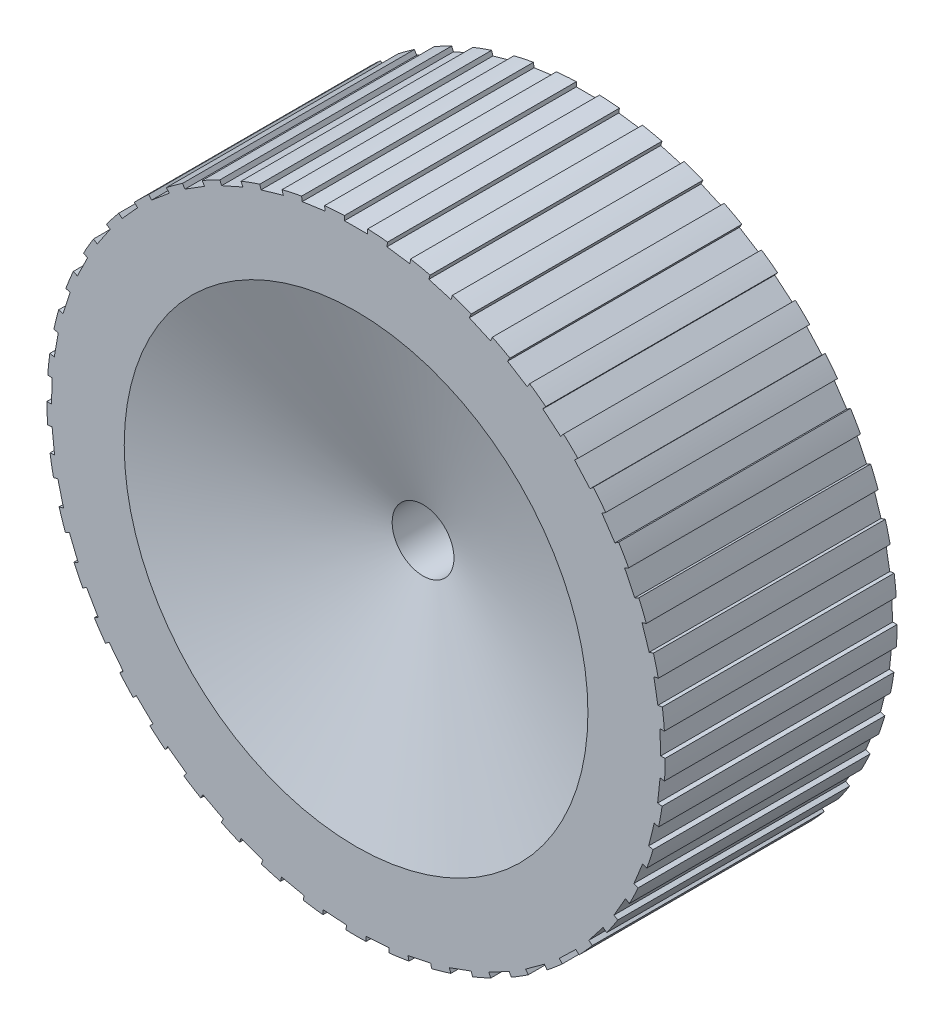
SolidWorks part; units mm, degrees
ref_plane "Front Plane" through (0, 0, 0) normal (0, 0, 1) x (1, 0, 0)
ref_plane "Top Plane" through (0, 0, 0) normal (0, 1, 0) x (1, 0, 0)
ref_plane "Right Plane" through (0, 0, 0) normal (1, 0, 0) x (0, 0, -1)
sketch "Sketch1" plane through (0, 0, 0) normal (0, 0, 1) x (1, 0, 0)
  circle A0 centre (0, 0) radius 40
  circle A1 centre (0, 0) radius 4
  dimension "D1" = 80
  dimension "D2" = 8
extrude "Boss-Extrude1" add sketch "Sketch1" along normal blind 30
sketch "Sketch3" plane through (0, 0, 0) normal (1, 0, 0) x (0, 0, -1)
  line L0 (-15, 40) -> (-15, -40) construction
  line L1 (0, 40) -> (-30, 40) construction
  line L2 (-30, -40) -> (0, -40) construction
  line L3 (0, 0) -> (-30, 0) construction
  line L4 (-30, 40) -> (-30, -40) construction
  line L5 (-30, 30) -> (0, 30) construction
  line L6 (0, -40) -> (0, 40) construction
  line L7 (0, 30) -> (-10, 0)
  line L8 (0, 30) -> (2.6052, 27.3948)
  line L9 (2.6052, 27.3948) -> (2.6052, 0)
  line L10 (2.6052, 0) -> (-10, 0)
  line L11 (-32.6052, 0) -> (-20, 0)
  line L12 (-30, 30) -> (-20, 0)
  line L13 (-32.6052, 27.3948) -> (-32.6052, 0)
  line L14 (-30, 30) -> (-32.6052, 27.3948)
  dimension "D1" = 10
  dimension "D2" = 5
revolve "Cut-Revolve1" cut sketch "Sketch3" angle 360 about L10
sketch "Sketch4" plane through (0, 0, 30) normal (0, 0, 1) x (1, 0, 0)
  line L0 (0, 40) -> (0, -40) construction
  line L1 (7.1372, 40.0061) -> (6.9674, 38.7978)
  line L2 (-1.5, 40.6101) -> (1.5, 40.6101)
  line L3 (-1.5, 40.6101) -> (-1.5, 39.3899)
  line L4 (-1.5, 39.3899) -> (1.5, 39.3899)
  line L5 (1.5, 40.6101) -> (1.5, 39.3899)
  line L6 (-1.5, 40.6101) -> (1.5, 39.3899) construction
  line L7 (-1.5, 39.3899) -> (1.5, 40.6101) construction
  line L8 (3.9966, 39.2153) -> (6.9674, 38.7978)
  line L9 (4.1664, 40.4236) -> (3.9966, 39.2153)
  line L10 (4.1664, 40.4236) -> (7.1372, 40.0061)
  line L11 (12.6356, 38.6235) -> (12.2992, 37.4505)
  line L12 (9.4154, 38.2775) -> (12.2992, 37.4505)
  line L13 (9.7518, 39.4504) -> (9.4154, 38.2775)
  line L14 (9.7518, 39.4504) -> (12.6356, 38.6235)
  line L15 (17.8879, 36.4891) -> (17.3916, 35.3744)
  line L16 (14.651, 36.5946) -> (17.3916, 35.3744)
  line L17 (15.1473, 37.7093) -> (14.651, 36.5946)
  line L18 (15.1473, 37.7093) -> (17.8879, 36.4891)
  line L19 (22.7921, 33.6444) -> (22.1455, 32.6096)
  line L20 (19.6014, 34.1994) -> (22.1455, 32.6096)
  line L21 (20.248, 35.2342) -> (19.6014, 34.1994)
  line L22 (20.248, 35.2342) -> (22.7921, 33.6444)
  line L23 (27.2527, 30.145) -> (26.4684, 29.2102)
  line L24 (24.1703, 31.1386) -> (26.4684, 29.2102)
  line L25 (24.9546, 32.0733) -> (24.1703, 31.1386)
  line L26 (24.9546, 32.0733) -> (27.2527, 30.145)
  line L27 (31.1829, 26.0587) -> (30.2761, 25.2423)
  line L28 (28.2687, 27.4717) -> (30.2761, 25.2423)
  line L29 (29.1755, 28.2882) -> (28.2687, 27.4717)
  line L30 (29.1755, 28.2882) -> (31.1829, 26.0587)
  line L31 (34.5061, 21.4653) -> (33.4945, 20.783)
  line L32 (31.8169, 23.2701) -> (33.4945, 20.783)
  line L33 (32.8285, 23.9524) -> (31.8169, 23.2701)
  line L34 (32.8285, 23.9524) -> (34.5061, 21.4653)
  line L35 (37.1577, 16.4541) -> (36.061, 15.9192)
  line L36 (34.7458, 18.6156) -> (36.061, 15.9192)
  line L37 (35.8426, 19.1505) -> (34.7458, 18.6156)
  line L38 (35.8426, 19.1505) -> (37.1577, 16.4541)
  line L39 (39.086, 11.1226) -> (37.9255, 10.7456)
  line L40 (36.9985, 13.5987) -> (37.9255, 10.7456)
  line L41 (38.159, 13.9758) -> (36.9985, 13.5987)
  line L42 (38.159, 13.9758) -> (39.086, 11.1226)
  line L43 (40.2536, 5.5747) -> (39.0519, 5.3628)
  line L44 (38.531, 8.3172) -> (39.0519, 5.3628)
  line L45 (39.7327, 8.5291) -> (38.531, 8.3172)
  line L46 (39.7327, 8.5291) -> (40.2536, 5.5747)
  line L47 (40.6377, -0.0818) -> (39.4183, -0.1244)
  line L48 (39.3136, 2.8738) -> (39.4183, -0.1244)
  line L49 (40.533, 2.9164) -> (39.3136, 2.8738)
  line L50 (40.533, 2.9164) -> (40.6377, -0.0818)
  line L51 (40.2308, -5.7367) -> (39.0173, -5.6091)
  line L52 (39.3309, -2.6256) -> (39.0173, -5.6091)
  line L53 (40.5444, -2.7531) -> (39.3309, -2.6256)
  line L54 (40.5444, -2.7531) -> (40.2308, -5.7367)
  line L55 (39.0409, -11.2799) -> (37.857, -10.9847)
  line L56 (38.5827, -8.0738) -> (37.857, -10.9847)
  line L57 (39.7667, -8.369) -> (38.5827, -8.0738)
  line L58 (39.7667, -8.369) -> (39.0409, -11.2799)
  line L59 (37.0911, -16.6036) -> (35.9598, -16.1465)
  line L60 (37.0836, -13.3649) -> (35.9598, -16.1465)
  line L61 (38.2149, -13.822) -> (37.0836, -13.3649)
  line L62 (38.2149, -13.822) -> (37.0911, -16.6036)
  line L63 (34.4194, -21.6041) -> (33.3627, -20.994)
  line L64 (34.8627, -18.3959) -> (33.3627, -20.994)
  line L65 (35.9194, -19.006) -> (34.8627, -18.3959)
  line L66 (35.9194, -19.006) -> (34.4194, -21.6041)
  line L67 (31.0777, -26.1841) -> (30.1162, -25.4329)
  line L68 (31.9632, -23.0688) -> (30.1162, -25.4329)
  line L69 (32.9247, -23.8201) -> (31.9632, -23.0688)
  line L70 (32.9247, -23.8201) -> (31.0777, -26.1841)
  line L71 (27.1311, -30.2544) -> (26.2835, -29.3767)
  line L72 (28.4415, -27.2927) -> (26.2835, -29.3767)
  line L73 (29.2892, -28.1705) -> (28.4415, -27.2927)
  line L74 (29.2892, -28.1705) -> (27.1311, -30.2544)
  line L75 (22.6565, -33.7359) -> (21.9393, -32.7488)
  line L76 (24.3663, -30.9854) -> (21.9393, -32.7488)
  line L77 (25.0835, -31.9726) -> (24.3663, -30.9854)
  line L78 (25.0835, -31.9726) -> (22.6565, -33.7359)
  line L79 (17.7409, -36.5608) -> (17.168, -35.4834)
  line L80 (19.8169, -34.075) -> (17.168, -35.4834)
  line L81 (20.3897, -35.1524) -> (19.8169, -34.075)
  line L82 (20.3897, -35.1524) -> (17.7409, -36.5608)
  line L83 (12.4799, -38.674) -> (12.0626, -37.5274)
  line L84 (14.8817, -36.5014) -> (12.0626, -37.5274)
  line L85 (15.299, -37.648) -> (14.8817, -36.5014)
  line L86 (15.299, -37.648) -> (12.4799, -38.674)
  line L87 (6.9761, -40.0345) -> (6.7224, -38.841)
  line L88 (9.6568, -38.2173) -> (6.7224, -38.841)
  line L89 (9.9105, -39.4108) -> (9.6568, -38.2173)
  line L90 (9.9105, -39.4108) -> (6.9761, -40.0345)
  line L91 (1.3365, -40.6158) -> (1.2514, -39.3986)
  line L92 (4.244, -39.1893) -> (1.2514, -39.3986)
  line L93 (4.3292, -40.4065) -> (4.244, -39.1893)
  line L94 (4.3292, -40.4065) -> (1.3365, -40.6158)
  line L95 (-4.3292, -40.4065) -> (-4.244, -39.1893)
  line L96 (-1.2514, -39.3986) -> (-4.244, -39.1893)
  line L97 (-1.3365, -40.6158) -> (-1.2514, -39.3986)
  line L98 (-1.3365, -40.6158) -> (-4.3292, -40.4065)
  line L99 (-9.9105, -39.4108) -> (-9.6568, -38.2173)
  line L100 (-6.7224, -38.841) -> (-9.6568, -38.2173)
  line L101 (-6.9761, -40.0345) -> (-6.7224, -38.841)
  line L102 (-6.9761, -40.0345) -> (-9.9105, -39.4108)
  line L103 (-15.299, -37.648) -> (-14.8817, -36.5014)
  line L104 (-12.0626, -37.5274) -> (-14.8817, -36.5014)
  line L105 (-12.4799, -38.674) -> (-12.0626, -37.5274)
  line L106 (-12.4799, -38.674) -> (-15.299, -37.648)
  line L107 (-20.3897, -35.1524) -> (-19.8169, -34.075)
  line L108 (-17.168, -35.4834) -> (-19.8169, -34.075)
  line L109 (-17.7409, -36.5608) -> (-17.168, -35.4834)
  line L110 (-17.7409, -36.5608) -> (-20.3897, -35.1524)
  line L111 (-25.0835, -31.9726) -> (-24.3663, -30.9854)
  line L112 (-21.9393, -32.7488) -> (-24.3663, -30.9854)
  line L113 (-22.6565, -33.7359) -> (-21.9393, -32.7488)
  line L114 (-22.6565, -33.7359) -> (-25.0835, -31.9726)
  line L115 (-29.2892, -28.1705) -> (-28.4415, -27.2927)
  line L116 (-26.2835, -29.3767) -> (-28.4415, -27.2927)
  line L117 (-27.1311, -30.2544) -> (-26.2835, -29.3767)
  line L118 (-27.1311, -30.2544) -> (-29.2892, -28.1705)
  line L119 (-32.9247, -23.8201) -> (-31.9632, -23.0688)
  line L120 (-30.1162, -25.4329) -> (-31.9632, -23.0688)
  line L121 (-31.0777, -26.1841) -> (-30.1162, -25.4329)
  line L122 (-31.0777, -26.1841) -> (-32.9247, -23.8201)
  line L123 (-35.9194, -19.006) -> (-34.8627, -18.3959)
  line L124 (-33.3627, -20.994) -> (-34.8627, -18.3959)
  line L125 (-34.4194, -21.6041) -> (-33.3627, -20.994)
  line L126 (-34.4194, -21.6041) -> (-35.9194, -19.006)
  line L127 (-38.2149, -13.822) -> (-37.0836, -13.3649)
  line L128 (-35.9598, -16.1465) -> (-37.0836, -13.3649)
  line L129 (-37.0911, -16.6036) -> (-35.9598, -16.1465)
  line L130 (-37.0911, -16.6036) -> (-38.2149, -13.822)
  line L131 (-39.7667, -8.369) -> (-38.5827, -8.0738)
  line L132 (-37.857, -10.9847) -> (-38.5827, -8.0738)
  line L133 (-39.0409, -11.2799) -> (-37.857, -10.9847)
  line L134 (-39.0409, -11.2799) -> (-39.7667, -8.369)
  line L135 (-40.5444, -2.7531) -> (-39.3309, -2.6256)
  line L136 (-39.0173, -5.6091) -> (-39.3309, -2.6256)
  line L137 (-40.2308, -5.7367) -> (-39.0173, -5.6091)
  line L138 (-40.2308, -5.7367) -> (-40.5444, -2.7531)
  line L139 (-40.533, 2.9164) -> (-39.3136, 2.8738)
  line L140 (-39.4183, -0.1244) -> (-39.3136, 2.8738)
  line L141 (-40.6377, -0.0818) -> (-39.4183, -0.1244)
  line L142 (-40.6377, -0.0818) -> (-40.533, 2.9164)
  line L143 (-39.7327, 8.5291) -> (-38.531, 8.3172)
  line L144 (-39.0519, 5.3628) -> (-38.531, 8.3172)
  line L145 (-40.2536, 5.5747) -> (-39.0519, 5.3628)
  line L146 (-40.2536, 5.5747) -> (-39.7327, 8.5291)
  line L147 (-38.159, 13.9758) -> (-36.9985, 13.5987)
  line L148 (-37.9255, 10.7456) -> (-36.9985, 13.5987)
  line L149 (-39.086, 11.1226) -> (-37.9255, 10.7456)
  line L150 (-39.086, 11.1226) -> (-38.159, 13.9758)
  line L151 (-35.8426, 19.1505) -> (-34.7458, 18.6156)
  line L152 (-36.061, 15.9192) -> (-34.7458, 18.6156)
  line L153 (-37.1577, 16.4541) -> (-36.061, 15.9192)
  line L154 (-37.1577, 16.4541) -> (-35.8426, 19.1505)
  line L155 (-32.8285, 23.9524) -> (-31.8169, 23.2701)
  line L156 (-33.4945, 20.783) -> (-31.8169, 23.2701)
  line L157 (-34.5061, 21.4653) -> (-33.4945, 20.783)
  line L158 (-34.5061, 21.4653) -> (-32.8285, 23.9524)
  line L159 (-29.1755, 28.2882) -> (-28.2687, 27.4717)
  line L160 (-30.2761, 25.2423) -> (-28.2687, 27.4717)
  line L161 (-31.1829, 26.0587) -> (-30.2761, 25.2423)
  line L162 (-31.1829, 26.0587) -> (-29.1755, 28.2882)
  line L163 (-24.9546, 32.0733) -> (-24.1703, 31.1386)
  line L164 (-26.4684, 29.2102) -> (-24.1703, 31.1386)
  line L165 (-27.2527, 30.145) -> (-26.4684, 29.2102)
  line L166 (-27.2527, 30.145) -> (-24.9546, 32.0733)
  line L167 (-20.248, 35.2342) -> (-19.6014, 34.1994)
  line L168 (-22.1455, 32.6096) -> (-19.6014, 34.1994)
  line L169 (-22.7921, 33.6444) -> (-22.1455, 32.6096)
  line L170 (-22.7921, 33.6444) -> (-20.248, 35.2342)
  line L171 (-15.1473, 37.7093) -> (-14.651, 36.5946)
  line L172 (-17.3916, 35.3744) -> (-14.651, 36.5946)
  line L173 (-17.8879, 36.4891) -> (-17.3916, 35.3744)
  line L174 (-17.8879, 36.4891) -> (-15.1473, 37.7093)
  line L175 (-9.7518, 39.4504) -> (-9.4154, 38.2775)
  line L176 (-12.2992, 37.4505) -> (-9.4154, 38.2775)
  line L177 (-12.6356, 38.6235) -> (-12.2992, 37.4505)
  line L178 (-12.6356, 38.6235) -> (-9.7518, 39.4504)
  line L179 (-4.1664, 40.4236) -> (-3.9966, 39.2153)
  line L180 (-6.9674, 38.7978) -> (-3.9966, 39.2153)
  line L181 (-7.1372, 40.0061) -> (-6.9674, 38.7978)
  line L182 (-7.1372, 40.0061) -> (-4.1664, 40.4236)
  circle A0 centre (0, 0) radius 40 construction
  point P187 (0, 0)
  dimension "D1" = 3
  dimension "D2" = 45
extrude "Cut-Extrude1" cut sketch "Sketch4" against normal through all
